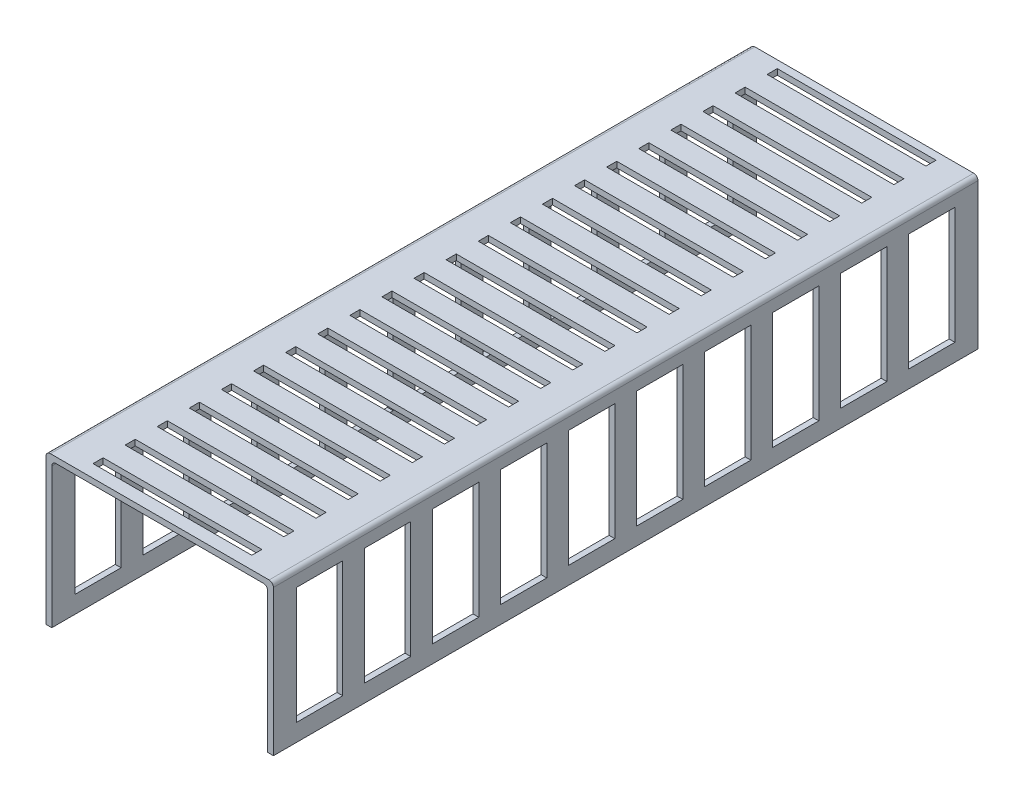
SolidWorks part; units mm, degrees
material "Nylon 101"
ref_plane "Front Plane" through (0, 0, 0) normal (0, 0, 1) x (1, 0, 0)
ref_plane "Top Plane" through (0, 0, 0) normal (0, 1, 0) x (1, 0, 0)
ref_plane "Right Plane" through (0, 0, 0) normal (1, 0, 0) x (0, 0, -1)
sketch "Sketch2" plane through (0, 27271.8493, 0) normal (0, 1, 0) x (1, 0, 0)
  line L0 (-34.7, 125.2786) -> (-34.7, 121.7786)
  line L5 (-34.7, 121.7786) -> (20.3, 121.7786)
  line L6 (-34.7, 125.2786) -> (20.3, 125.2786)
  line L7 (20.3, 125.2786) -> (20.3, 121.7786)
  line L9 (-46.6, 139.05) -> (32.2, 139.05)
  line L10 (-46.6, 139.05) -> (-46.6, -105.05)
  line L11 (-46.6, -105.05) -> (32.2, -105.05)
  line L12 (32.2, 139.05) -> (32.2, -105.05)
  line L13 (-49.2, -106.05) -> (34.8, -106.05) construction
  line L17 (33.2179, 134.65) -> (30.05, 134.65) construction
  line L18 (30.05, 129.75) -> (30.05, 135.7) construction
  line L19 (-38.7, 144.3) -> (-38.7, 136.4) construction
  line L20 (-34.7, 136.4) -> (20.3, 136.4)
  line L21 (-34.7, 136.4) -> (-34.7, 132.9)
  line L22 (-34.7, 132.9) -> (20.3, 132.9)
  line L23 (20.3, 136.4) -> (20.3, 132.9)
  line L24 (-34.7, 136.4) -> (20.3, 132.9) construction
  line L25 (-34.7, 132.9) -> (20.3, 136.4) construction
  line L26 (-34.7, 114.1571) -> (-34.7, 110.6571)
  line L27 (-34.7, 110.6571) -> (20.3, 110.6571)
  line L28 (-34.7, 114.1571) -> (20.3, 114.1571)
  line L29 (20.3, 114.1571) -> (20.3, 110.6571)
  line L30 (-34.7, 103.0357) -> (-34.7, 99.5357)
  line L31 (-34.7, 99.5357) -> (20.3, 99.5357)
  line L32 (-34.7, 103.0357) -> (20.3, 103.0357)
  line L33 (20.3, 103.0357) -> (20.3, 99.5357)
  line L34 (-34.7, 91.9143) -> (-34.7, 88.4143)
  line L35 (-34.7, 88.4143) -> (20.3, 88.4143)
  line L36 (-34.7, 91.9143) -> (20.3, 91.9143)
  line L37 (20.3, 91.9143) -> (20.3, 88.4143)
  line L38 (-34.7, 80.7929) -> (-34.7, 77.2929)
  line L39 (-34.7, 77.2929) -> (20.3, 77.2929)
  line L40 (-34.7, 80.7929) -> (20.3, 80.7929)
  line L41 (20.3, 80.7929) -> (20.3, 77.2929)
  line L42 (-34.7, 69.6714) -> (-34.7, 66.1714)
  line L43 (-34.7, 66.1714) -> (20.3, 66.1714)
  line L44 (-34.7, 69.6714) -> (20.3, 69.6714)
  line L45 (20.3, 69.6714) -> (20.3, 66.1714)
  line L46 (-34.7, 58.55) -> (-34.7, 55.05)
  line L47 (-34.7, 55.05) -> (20.3, 55.05)
  line L48 (-34.7, 58.55) -> (20.3, 58.55)
  line L49 (20.3, 58.55) -> (20.3, 55.05)
  line L50 (-34.7, 47.4286) -> (-34.7, 43.9286)
  line L51 (-34.7, 43.9286) -> (20.3, 43.9286)
  line L52 (-34.7, 47.4286) -> (20.3, 47.4286)
  line L53 (20.3, 47.4286) -> (20.3, 43.9286)
  line L54 (-34.7, 36.3071) -> (-34.7, 32.8071)
  line L55 (-34.7, 32.8071) -> (20.3, 32.8071)
  line L56 (-34.7, 36.3071) -> (20.3, 36.3071)
  line L57 (20.3, 36.3071) -> (20.3, 32.8071)
  line L58 (-34.7, 25.1857) -> (-34.7, 21.6857)
  line L59 (-34.7, 21.6857) -> (20.3, 21.6857)
  line L60 (-34.7, 25.1857) -> (20.3, 25.1857)
  line L61 (20.3, 25.1857) -> (20.3, 21.6857)
  line L62 (-34.7, 14.0643) -> (-34.7, 10.5643)
  line L63 (-34.7, 10.5643) -> (20.3, 10.5643)
  line L64 (-34.7, 14.0643) -> (20.3, 14.0643)
  line L65 (20.3, 14.0643) -> (20.3, 10.5643)
  line L66 (-34.7, 2.9429) -> (-34.7, -0.5571)
  line L67 (-34.7, -0.5571) -> (20.3, -0.5571)
  line L68 (-34.7, 2.9429) -> (20.3, 2.9429)
  line L69 (20.3, 2.9429) -> (20.3, -0.5571)
  line L70 (-34.7, -8.1786) -> (-34.7, -11.6786)
  line L71 (-34.7, -11.6786) -> (20.3, -11.6786)
  line L72 (-34.7, -8.1786) -> (20.3, -8.1786)
  line L73 (20.3, -8.1786) -> (20.3, -11.6786)
  line L74 (-34.7, -19.3) -> (-34.7, -22.8)
  line L75 (-34.7, -22.8) -> (20.3, -22.8)
  line L76 (-34.7, -19.3) -> (20.3, -19.3)
  line L77 (20.3, -19.3) -> (20.3, -22.8)
  line L78 (-34.7, -30.4214) -> (-34.7, -33.9214)
  line L79 (-34.7, -33.9214) -> (20.3, -33.9214)
  line L80 (-34.7, -30.4214) -> (20.3, -30.4214)
  line L81 (20.3, -30.4214) -> (20.3, -33.9214)
  line L82 (-34.7, -41.5429) -> (-34.7, -45.0429)
  line L83 (-34.7, -45.0429) -> (20.3, -45.0429)
  line L84 (-34.7, -41.5429) -> (20.3, -41.5429)
  line L85 (20.3, -41.5429) -> (20.3, -45.0429)
  line L86 (-34.7, -52.6643) -> (-34.7, -56.1643)
  line L87 (-34.7, -56.1643) -> (20.3, -56.1643)
  line L88 (-34.7, -52.6643) -> (20.3, -52.6643)
  line L89 (20.3, -52.6643) -> (20.3, -56.1643)
  line L90 (-34.7, -63.7857) -> (-34.7, -67.2857)
  line L91 (-34.7, -67.2857) -> (20.3, -67.2857)
  line L92 (-34.7, -63.7857) -> (20.3, -63.7857)
  line L93 (20.3, -63.7857) -> (20.3, -67.2857)
  line L94 (-34.7, -74.9071) -> (-34.7, -78.4071)
  line L95 (-34.7, -78.4071) -> (20.3, -78.4071)
  line L96 (-34.7, -74.9071) -> (20.3, -74.9071)
  line L97 (20.3, -74.9071) -> (20.3, -78.4071)
  line L98 (-34.7, -86.0286) -> (-34.7, -89.5286)
  line L99 (-34.7, -89.5286) -> (20.3, -89.5286)
  line L100 (-34.7, -86.0286) -> (20.3, -86.0286)
  line L101 (20.3, -86.0286) -> (20.3, -89.5286)
  line L102 (-34.7, -97.15) -> (-34.7, -100.65)
  line L103 (-34.7, -100.65) -> (20.3, -100.65)
  line L104 (-34.7, -97.15) -> (20.3, -97.15)
  line L105 (20.3, -97.15) -> (20.3, -100.65)
  line L107 (-49.2, 140.05) -> (34.8, 140.05) construction
  line L108 (-47.2, -105.65) -> (-47.2, 139.65) construction
  line L109 (32.8, -105.65) -> (32.8, 139.65) construction
  point P21 (-7.2, 134.65)
  dimension "D1" = 1
  dimension "D2" = 1
  dimension "D3" = 0.6
  dimension "D4" = 0.6
  dimension "D5" = 4
  dimension "D6" = 3.5
  dimension "D8" = 4.4
  dimension "D9" = 4.4
  dimension "D7" = 22
extrude "Boss-Extrude1" add sketch "Sketch2" along normal blind 2
sketch "Sketch3" plane through (0, 27271.8493, 0) normal (0, -1, 0) x (1, 0, 0)
  line L0 (32.2, -139.05) -> (-46.6, -139.05) construction
  line L1 (-46.6, 105.05) -> (-44.6, 105.05)
  line L2 (-46.6, 105.05) -> (-46.6, -139.05)
  line L3 (-46.6, -139.05) -> (-44.6, -139.05)
  line L4 (-44.6, 105.05) -> (-44.6, -139.05)
  line L5 (-7.2, 105.05) -> (-7.2, -2.7153) construction
  line L6 (-46.6, 105.05) -> (32.2, 105.05) construction
  line L7 (30.2, 105.05) -> (30.2, -139.05)
  line L8 (32.2, -139.05) -> (30.2, -139.05)
  line L9 (32.2, 105.05) -> (32.2, -139.05)
  line L10 (32.2, 105.05) -> (30.2, 105.05)
  dimension "D1" = 2
extrude "Boss-Extrude2" add sketch "Sketch3" along normal blind 50
fillet "Fillet1" radius 1.5 4 edges at (-44.6, 27271.8493, -17) (-46.6, 27273.8493, -17) (30.2, 27271.8493, -17) (32.2, 27273.8493, -17)
sketch "Sketch4" plane through (32.2, 0, 0) normal (1, 0, 0) x (0, 0, -1)
  line L0 (-105.05, 27272.3493) -> (-105.05, 27221.8493) construction
  line L1 (-97.05, 27268.3493) -> (-81.05, 27268.3493)
  line L2 (-97.05, 27268.3493) -> (-97.05, 27227.8493)
  line L3 (-97.05, 27227.8493) -> (-81.05, 27227.8493)
  line L4 (-81.05, 27268.3493) -> (-81.05, 27227.8493)
  line L5 (139.05, 27272.3493) -> (-105.05, 27272.3493) construction
  line L6 (139.05, 27221.8493) -> (-105.05, 27221.8493) construction
  line L7 (-73.4833, 27268.3493) -> (-57.4833, 27268.3493)
  line L8 (-73.4833, 27268.3493) -> (-73.4833, 27227.8493)
  line L9 (-73.4833, 27227.8493) -> (-57.4833, 27227.8493)
  line L10 (-57.4833, 27268.3493) -> (-57.4833, 27227.8493)
  line L11 (-49.9167, 27268.3493) -> (-33.9167, 27268.3493)
  line L12 (-49.9167, 27268.3493) -> (-49.9167, 27227.8493)
  line L13 (-49.9167, 27227.8493) -> (-33.9167, 27227.8493)
  line L14 (-33.9167, 27268.3493) -> (-33.9167, 27227.8493)
  line L15 (-26.35, 27268.3493) -> (-10.35, 27268.3493)
  line L16 (-26.35, 27268.3493) -> (-26.35, 27227.8493)
  line L17 (-26.35, 27227.8493) -> (-10.35, 27227.8493)
  line L18 (-10.35, 27268.3493) -> (-10.35, 27227.8493)
  line L19 (-2.7833, 27268.3493) -> (13.2167, 27268.3493)
  line L20 (-2.7833, 27268.3493) -> (-2.7833, 27227.8493)
  line L21 (-2.7833, 27227.8493) -> (13.2167, 27227.8493)
  line L22 (13.2167, 27268.3493) -> (13.2167, 27227.8493)
  line L23 (20.7833, 27268.3493) -> (36.7833, 27268.3493)
  line L24 (20.7833, 27268.3493) -> (20.7833, 27227.8493)
  line L25 (20.7833, 27227.8493) -> (36.7833, 27227.8493)
  line L26 (36.7833, 27268.3493) -> (36.7833, 27227.8493)
  line L27 (44.35, 27268.3493) -> (60.35, 27268.3493)
  line L28 (44.35, 27268.3493) -> (44.35, 27227.8493)
  line L29 (44.35, 27227.8493) -> (60.35, 27227.8493)
  line L30 (60.35, 27268.3493) -> (60.35, 27227.8493)
  line L31 (67.9167, 27268.3493) -> (83.9167, 27268.3493)
  line L32 (67.9167, 27268.3493) -> (67.9167, 27227.8493)
  line L33 (67.9167, 27227.8493) -> (83.9167, 27227.8493)
  line L34 (83.9167, 27268.3493) -> (83.9167, 27227.8493)
  line L35 (91.4833, 27268.3493) -> (107.4833, 27268.3493)
  line L36 (91.4833, 27268.3493) -> (91.4833, 27227.8493)
  line L37 (91.4833, 27227.8493) -> (107.4833, 27227.8493)
  line L38 (107.4833, 27268.3493) -> (107.4833, 27227.8493)
  line L39 (115.05, 27268.3493) -> (131.05, 27268.3493)
  line L40 (115.05, 27268.3493) -> (115.05, 27227.8493)
  line L41 (115.05, 27227.8493) -> (131.05, 27227.8493)
  line L42 (131.05, 27268.3493) -> (131.05, 27227.8493)
  line L43 (139.05, 27272.3493) -> (139.05, 27221.8493) construction
  dimension "D1" = 8
  dimension "D2" = 4
  dimension "D3" = 6
  dimension "D4" = 16
  dimension "D6" = 8
  dimension "D5" = 10
extrude "Cut-Extrude1" cut sketch "Sketch4" against normal through all
